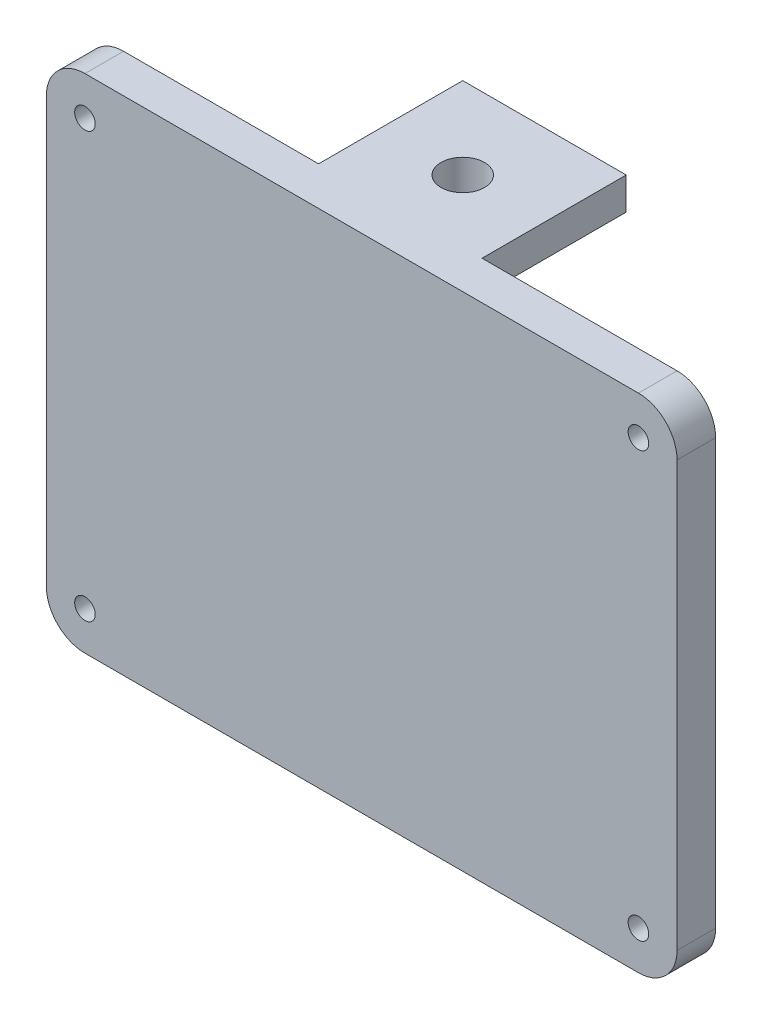
SolidWorks part; units mm, degrees
ref_plane "Front Plane" through (0, 0, 0) normal (0, 0, 1) x (1, 0, 0)
ref_plane "Top Plane" through (0, 0, 0) normal (0, 1, 0) x (1, 0, 0)
ref_plane "Right Plane" through (0, 0, 0) normal (1, 0, 0) x (0, 0, -1)
sketch "Sketch1" plane through (0, 0, 0) normal (0, 1, 0) x (1, 0, 0)
  line L1 (-12.7, 12.7) -> (12.7, 12.7)
  line L2 (-12.7, 12.7) -> (-12.7, -12.7)
  line L3 (-12.7, -12.7) -> (12.7, -12.7)
  line L4 (12.7, 12.7) -> (12.7, -12.7)
  line L5 (-12.7, 12.7) -> (12.7, -12.7) construction
  line L6 (-12.7, -12.7) -> (12.7, 12.7) construction
  point P0 (0, 0)
  dimension "D1" = 25.4
  dimension "D2" = 25.4
extrude "Boss-Extrude1" add sketch "Sketch1" along normal blind 5
hole_wizard "1/4 Clearance Hole1" positions "Sketch2" profile "Sketch3" hole size "1/4" standard "ANSI Inch" end condition through all
sketch "Sketch2" plane through (0, 5, 0) normal (0, 1, 0) x (1, 0, 0)
  point P0 (0, 0)
sketch "Sketch3" plane through (0, 5, 0) normal (1, 0, 0) x (0, 0, 1)
  line L0 (0, 0) -> (0, 5)
  line L1 (0, 5) -> (3.3782, 5)
  line L2 (3.3782, 5) -> (3.3782, 0)
  line L5 (3.3782, 0) -> (0, 0)
  line L11 (0, -6.35) -> (0, 107.95) construction
  dimension "Thru Hole Dia." = 6.7564
  dimension "Thru Hole Depth" = 5
sketch "Sketch4" plane through (0, 0, 12.7) normal (0, 0, 1) x (1, 0, 0)
  line L0 (-49, -73) -> (-49, 5)
  line L1 (-43, -67) -> (43, -67) construction
  line L2 (-43, -67) -> (-43, -1) construction
  line L3 (-43, -1) -> (43, -1) construction
  line L4 (43, -67) -> (43, -1) construction
  line L5 (-43, -67) -> (43, -1) construction
  line L6 (-43, -1) -> (43, -67) construction
  line L7 (-49, 5) -> (49, 5)
  line L8 (49, -73) -> (49, 5)
  line L9 (-49, -73) -> (49, -73)
  line L10 (-12.7, 5) -> (12.7, 5) construction
  circle A0 centre (-43, -1) radius 1.6
  circle A1 centre (43, -1) radius 1.6
  circle A2 centre (43, -67) radius 1.6
  circle A3 centre (-43, -67) radius 1.6
  point P0 (0, -34)
  line M9 (-12.7, 0) -> (12.7, 0)
  line M10 (12.7, 0) -> (12.7, 5)
  line M11 (12.7, 5) -> (-12.7, 5)
  line M12 (-12.7, 5) -> (-12.7, 0)
  dimension "D4" = 3.2
  dimension "D1" = 6
  dimension "D2" = 86
  dimension "D3" = 66
extrude "Boss-Extrude2" add sketch "Sketch4" against normal mid plane 6 contours L0 L9 L8 L7 A3 A2 A1 A0 M10 M9 M12 | M12 M9 M10 M11
fillet "Fillet1" radius 6 4 edges at (49, -73, 12.7) (-49, -73, 12.7) (49, 5, 12.7) (-49, 5, 12.7)
